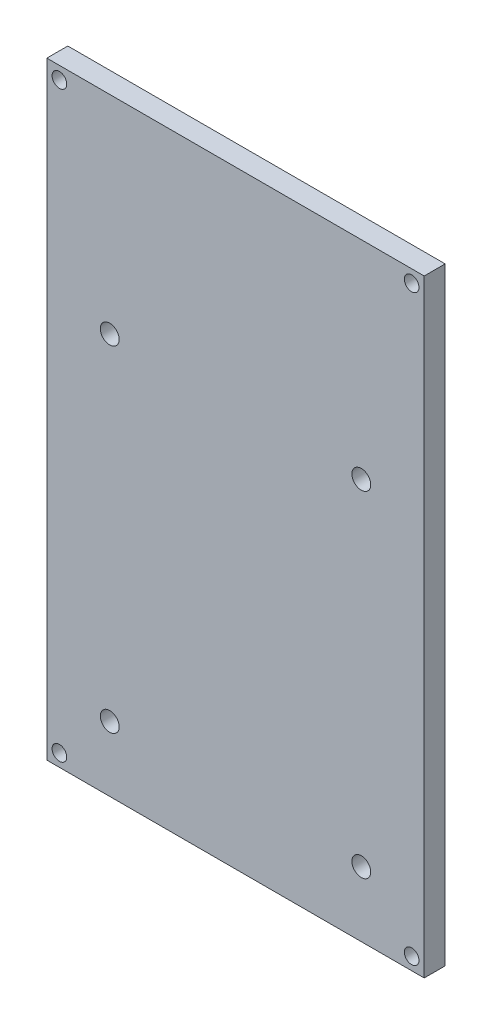
SolidWorks part; units mm, degrees
ref_plane "Front Plane" through (0, 0, 0) normal (0, 0, 1) x (1, 0, 0)
ref_plane "Top Plane" through (0, 0, 0) normal (0, 1, 0) x (1, 0, 0)
ref_plane "Right Plane" through (0, 0, 0) normal (1, 0, 0) x (0, 0, -1)
sketch "Sketch1" plane through (0, 0, 0) normal (0, 0, 1) x (1, 0, 0)
  line L1 (-45, -72.5) -> (45, -72.5)
  line L2 (-45, -72.5) -> (-45, 72.5)
  line L3 (-45, 72.5) -> (45, 72.5)
  line L4 (45, -72.5) -> (45, 72.5)
  line L5 (-45, -72.5) -> (45, 72.5) construction
  line L6 (-45, 72.5) -> (45, -72.5) construction
  point P0 (0, 0)
  dimension "D1" = 90
  dimension "D2" = 145
extrude "Boss-Extrude1" add sketch "Sketch1" along normal blind 5
sketch "Sketch2" plane through (0, 0, 0) normal (0, 0, -1) x (-1, 0, 0)
  line L0 (0, 0) -> (0, -72.5) construction
  line L1 (45, -72.5) -> (-45, -72.5) construction
  line L2 (0, 0) -> (45, 0) construction
  line L3 (45, 72.5) -> (45, -72.5) construction
  line L4 (-45, 72.5) -> (45, 72.5) construction
  line L5 (-45, -72.5) -> (-45, 72.5) construction
  circle A0 centre (-42, 69.5) radius 1.75
  circle A1 centre (-42, -69.5) radius 1.75
  circle A2 centre (42, 69.5) radius 1.75
  circle A3 centre (42, -69.5) radius 1.75
  dimension "D1" = 3
  dimension "D2" = 3
  dimension "D3" = 3.5
extrude "Cut-Extrude1" cut sketch "Sketch2" against normal through all
sketch "Sketch3" plane through (0, 0, 0) normal (0, 0, -1) x (-1, 0, 0)
  line L0 (0, 0) -> (0, -72.5) construction
  line L1 (45, -72.5) -> (-45, -72.5) construction
  line L2 (0, 0) -> (45, 0) construction
  line L3 (45, 72.5) -> (45, -72.5) construction
  line L4 (0, -17) -> (35, -17) construction
  line L5 (-35, -62) -> (35, -62) construction
  line L6 (-35, -62) -> (-35, 28) construction
  line L7 (-35, 28) -> (35, 28) construction
  line L8 (35, -62) -> (35, 28) construction
  line L9 (-35, -62) -> (35, 28) construction
  line L10 (-35, 28) -> (35, -62) construction
  circle A0 centre (-30, 23) radius 2.25
  circle A1 centre (30, 23) radius 2.25
  circle A2 centre (30, -57) radius 2.25
  circle A3 centre (-30, -57) radius 2.25
  point P5 (0, -17)
  dimension "D4" = 4.5
  dimension "D5" = 5
  dimension "D6" = 5
  dimension "D1" = 90
  dimension "D2" = 70
  dimension "D3" = 17
extrude "Cut-Extrude2" cut sketch "Sketch3" against normal through all
